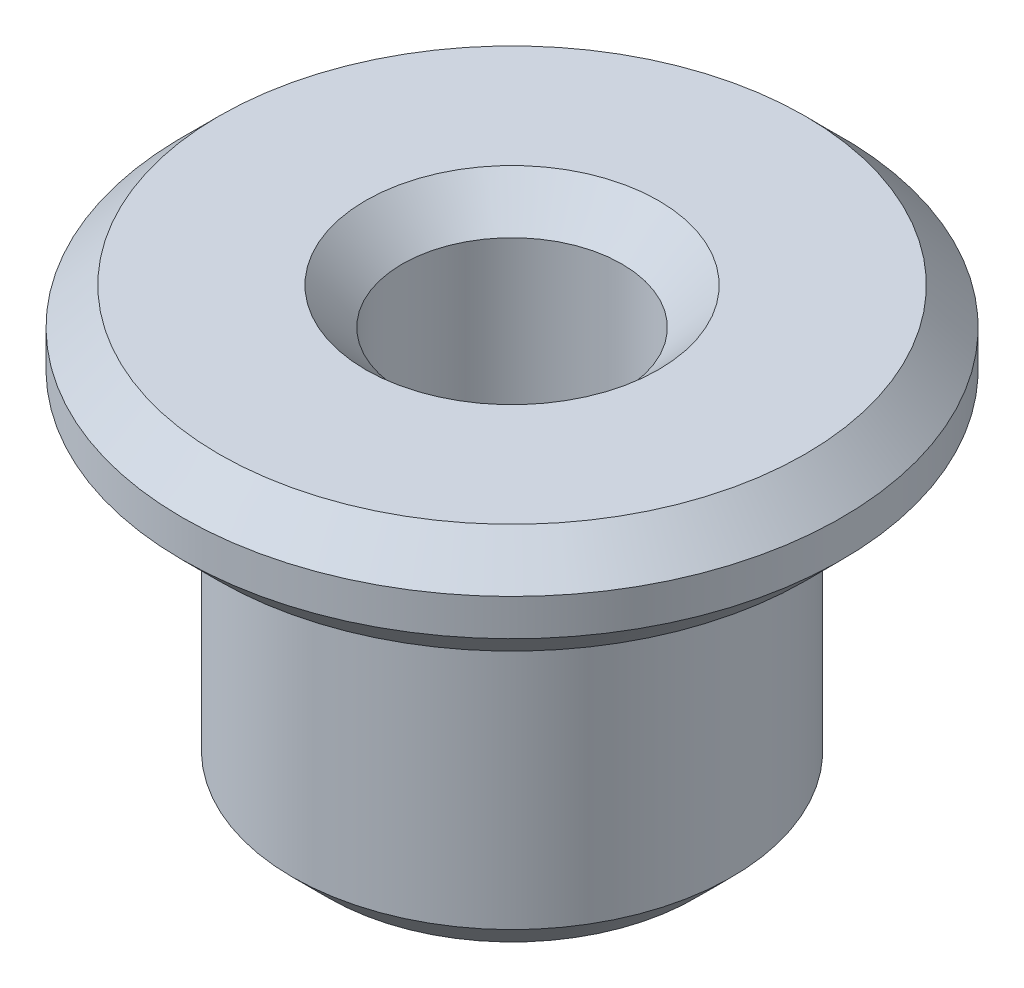
SolidWorks part; units mm, degrees
material "Bronze pour coussinet"
ref_plane "Plan de face" through (0, 0, 0) normal (0, 0, 1) x (1, 0, 0)
ref_plane "Plan de dessus" through (0, 0, 0) normal (0, 1, 0) x (1, 0, 0)
ref_plane "Plan de droite" through (0, 0, 0) normal (1, 0, 0) x (0, 0, -1)
sketch "Esquisse1" plane through (0, 0, 0) normal (0, 0, 1) x (1, 0, 0)
  line L0 (0, 0) -> (0, -75.7262) construction
  line L1 (2, 0) -> (4, 0)
  line L2 (4.5, -0.5) -> (4.5, -1)
  line L3 (4, -1.5) -> (3.5, -1.5)
  line L4 (3, -2) -> (3, -5.5)
  line L5 (2.5, -6) -> (2, -6)
  line L6 (1.5, -5.5) -> (1.5, -0.5)
  line L7 (1.5, -0.5) -> (2, 0)
  line L8 (4, 0) -> (4.5, -0.5)
  line L9 (4.5, -1) -> (4, -1.5)
  line L10 (3, -5.5) -> (2.5, -6)
  line L11 (2, -6) -> (1.5, -5.5)
  arc A0 (3.5, -1.5) -> (3, -2) centre (3.5, -2) ccw
  point P3 (1.5, 0)
  point P4 (4.5, 0)
  point P6 (4.5, -1.5)
  point P8 (3, -6)
  point P9 (1.5, -6)
  dimension "D14" = 0.5
  dimension "D1" = 3
  dimension "D2" = 6
  dimension "D3" = 9
  dimension "D4" = 0.5
  dimension "H1" = 1.5
  dimension "L1" = 6
  dimension "D5" = 45
  dimension "D6" = 0.5
  dimension "D7" = 45
  dimension "D8" = 0.5
  dimension "D9" = 45
  dimension "D10" = 0.5
  dimension "D11" = 45
  dimension "D12" = 0.5
  dimension "D13" = 45
revolve "Révolution1" add sketch "Esquisse1" angle 360 about L0
